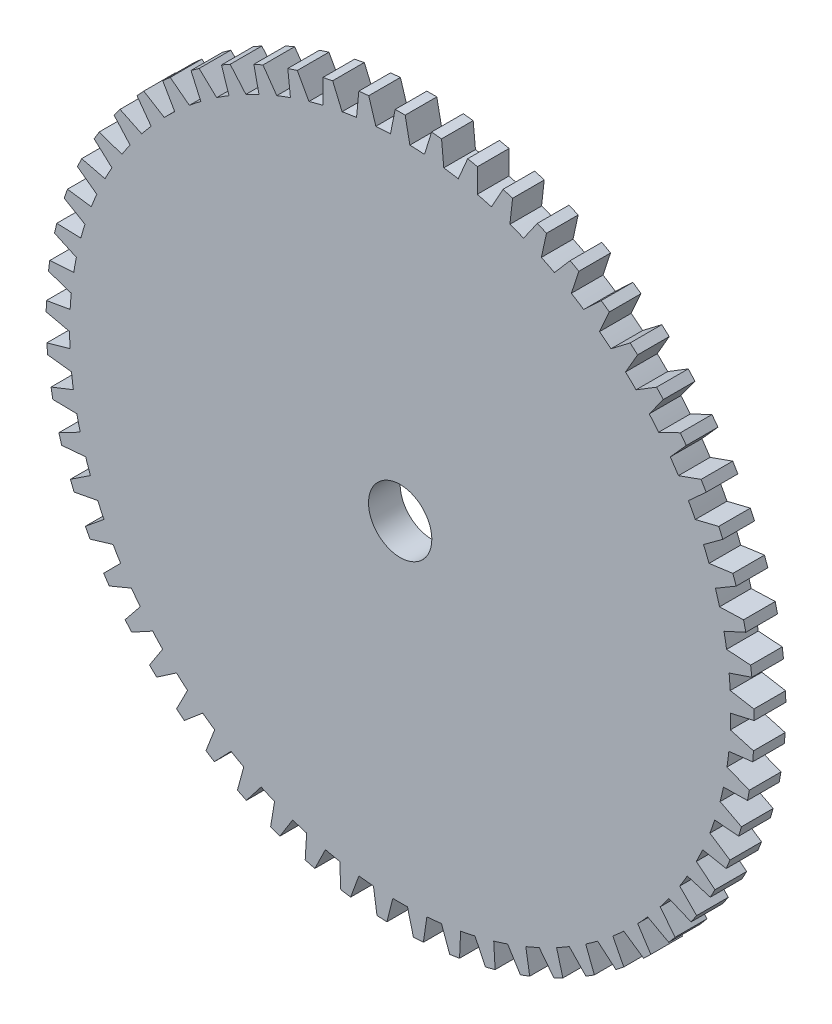
SolidWorks part; units mm, degrees
ref_plane "Front Plane" through (0, 0, 0) normal (0, 0, 1) x (1, 0, 0)
ref_plane "Top Plane" through (0, 0, 0) normal (0, 1, 0) x (1, 0, 0)
ref_plane "Right Plane" through (0, 0, 0) normal (1, 0, 0) x (0, 0, -1)
sketch "Sketch1" plane through (0, 0, 0) normal (0, 0, 1) x (1, 0, 0)
  circle A0 centre (0, 0) radius 33.1488
  dimension "D1" = 66.2976
extrude "Boss-Extrude1" add sketch "Sketch1" along normal blind 3.175
sketch "Sketch2" plane through (0, 0, 3.175) normal (0, 0, 1) x (1, 0, 0)
  circle A0 centre (0, 0) radius 3.175
  dimension "D1" = 6.35
extrude "Cut-Extrude1" cut sketch "Sketch2" against normal blind 3.175
sketch "Sketch3" plane through (0, 0, 3.175) normal (0, 0, 1) x (1, 0, 0)
  line L0 (0, 0) -> (0, 37.4939) construction
  line L1 (-1, 33) -> (1, 33)
  line L2 (1, 33) -> (0.5, 35.5)
  line L3 (0.5, 35.5) -> (-0.5, 35.5)
  line L4 (-0.5, 35.5) -> (-1, 33)
  point P5 (0, 35.5)
  point P8 (0, 33)
  dimension "D1" = 33
  dimension "D2" = 2.5
  dimension "D3" = 2
  dimension "D4" = 1
extrude "Boss-Extrude2" add sketch "Sketch3" against normal blind 3.175
pattern_circular "CirPattern4" count 61 over 360 about axis through (0, 0, 0) along (0, 0, 1) of "Boss-Extrude2"
